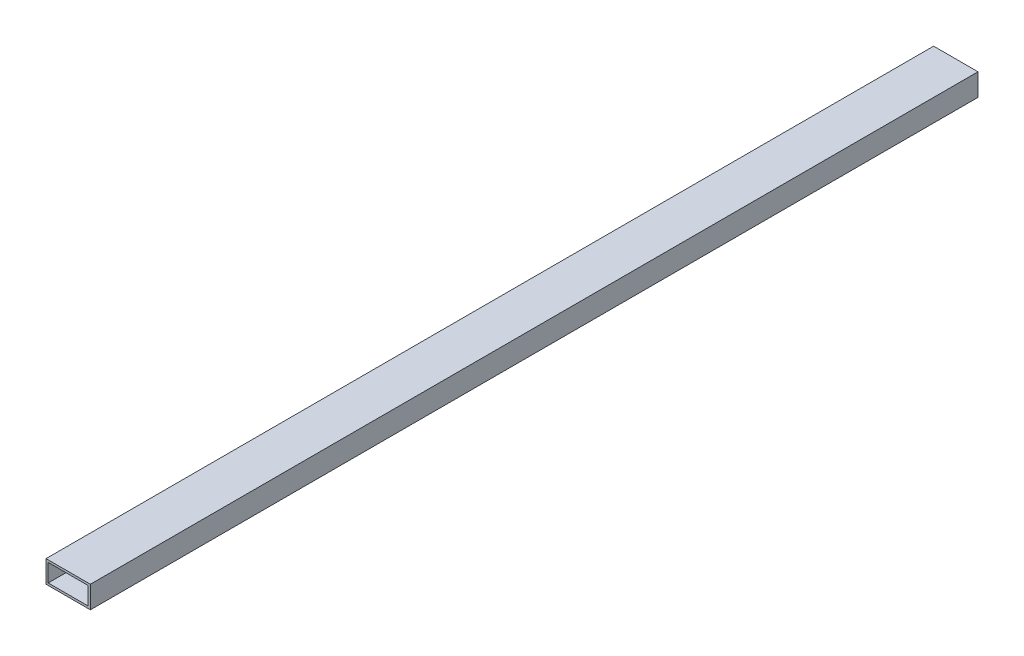
SolidWorks part; units mm, degrees
ref_plane "Спереди" through (0, 0, 0) normal (0, 0, 1) x (1, 0, 0)
ref_plane "Сверху" through (0, 0, 0) normal (0, 1, 0) x (1, 0, 0)
ref_plane "Справа" through (0, 0, 0) normal (1, 0, 0) x (0, 0, -1)
sketch "Эскиз1" plane through (0, 0, 0) normal (0, 0, 1) x (1, 0, 0)
  line L1 (-32.1255, -7.3604) -> (7.8745, -7.3604)
  line L2 (-32.1255, -7.3604) -> (-32.1255, -27.3604)
  line L3 (-32.1255, -27.3604) -> (7.8745, -27.3604)
  line L4 (7.8745, -7.3604) -> (7.8745, -27.3604)
  line L5 (-30.1255, -9.3604) -> (5.8745, -9.3604)
  line L6 (-30.1255, -9.3604) -> (-30.1255, -25.3604)
  line L7 (-30.1255, -25.3604) -> (5.8745, -25.3604)
  line L8 (5.8745, -9.3604) -> (5.8745, -25.3604)
  dimension "D1" = 40
  dimension "D2" = 20
  dimension "D3" = 2
  dimension "D4" = 2
  dimension "D5" = 2
  dimension "D6" = 2
extrude "Бобышка-Вытянуть1" add sketch "Эскиз1" along normal blind 800
